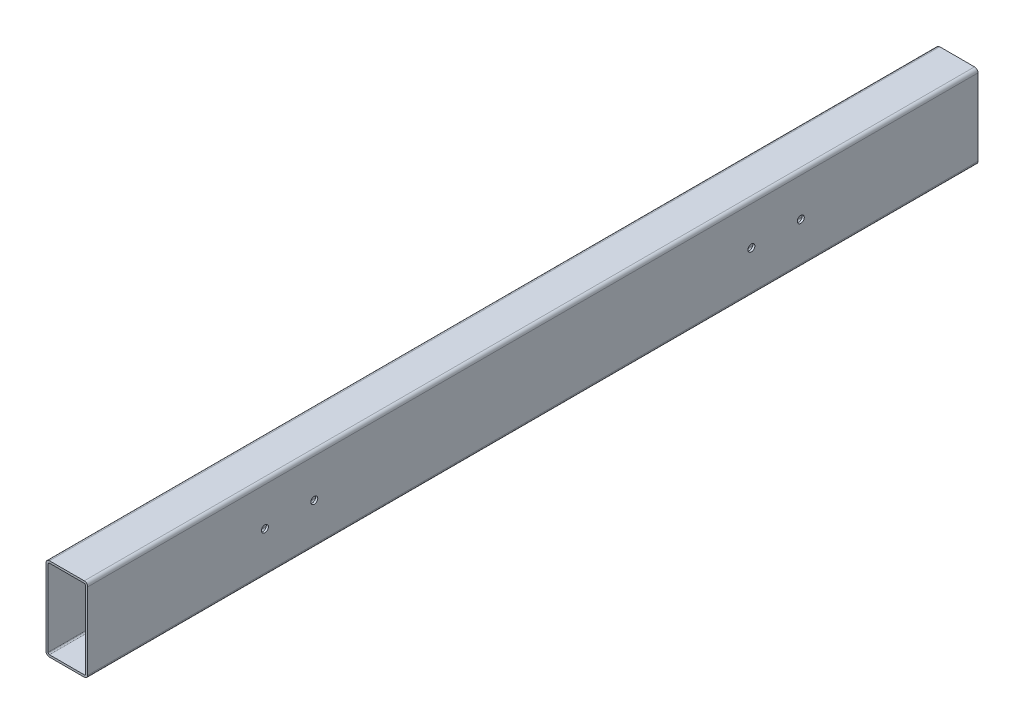
SolidWorks part; units mm, degrees
ref_plane "Front Plane" through (0, 0, 0) normal (0, 0, 1) x (1, 0, 0)
ref_plane "Top Plane" through (0, 0, 0) normal (0, 1, 0) x (1, 0, 0)
ref_plane "Right Plane" through (0, 0, 0) normal (1, 0, 0) x (0, 0, -1)
sketch "Sketch1" plane through (0, 0, 0) normal (0, 0, 1) x (1, 0, 0)
  line L1 (-25, -60) -> (25, -60)
  line L2 (-30, -55) -> (-30, 55)
  line L3 (-25, 60) -> (25, 60)
  line L4 (30, -55) -> (30, 55)
  line L5 (-30, -60) -> (30, 60) construction
  line L6 (-30, 60) -> (30, -60) construction
  arc A0 (-30, -55) -> (-25, -60) centre (-25, -55) ccw
  arc A1 (25, -60) -> (30, -55) centre (25, -55) ccw
  arc A2 (30, 55) -> (25, 60) centre (25, 55) ccw
  arc A3 (-25, 60) -> (-30, 55) centre (-25, 55) ccw
  point P0 (0, 0)
  dimension "D3" = 5
  dimension "D1" = 60
  dimension "D2" = 120
extrude "Extrude-Thin1" add sketch "Sketch1" along normal blind 640 and the other way blind 640 thin thin type one direction reverse wall 3
sketch "Sketch2" plane through (0, 0, 0) normal (1, 0, 0) x (0, 0, -1)
  line L0 (0, 33) -> (0, -33) construction
  circle A0 centre (-314.25, 0) radius 5
  circle A1 centre (-385.25, 0) radius 5
  circle A2 centre (314.25, 0) radius 5
  circle A3 centre (385.25, 0) radius 5
  dimension "D1" = 10
  dimension "D2" = 71
  dimension "D3" = 314.25
extrude "Cut-Extrude1" cut sketch "Sketch2" against normal through all both and the other way through all
